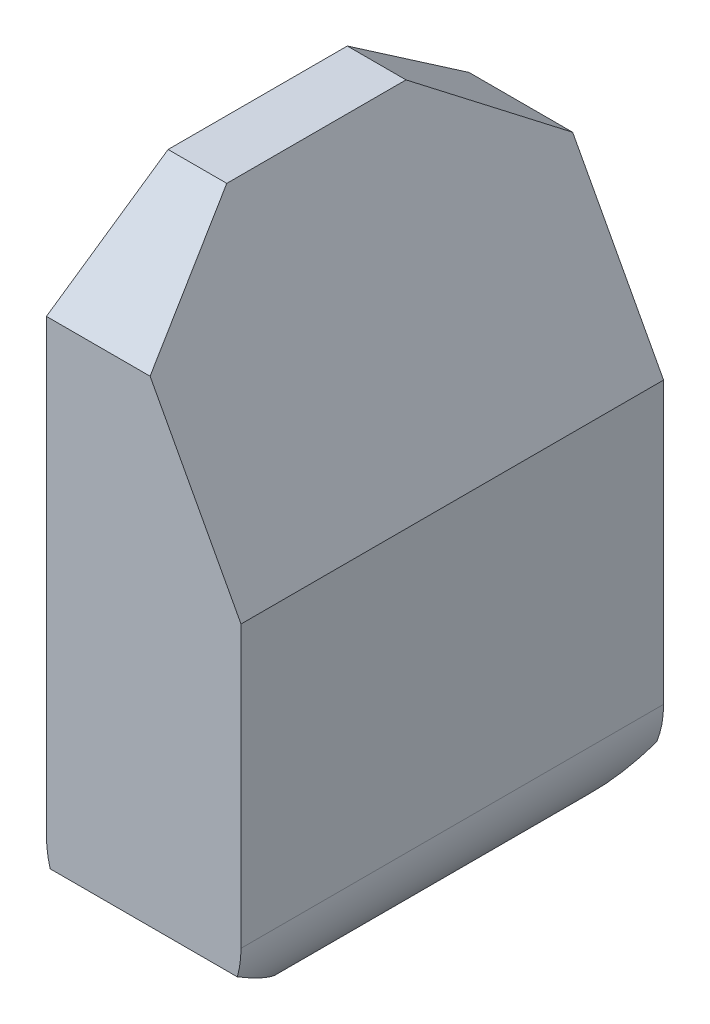
SolidWorks part; units mm, degrees
ref_plane "Front" through (0, 0, 0) normal (0, 0, 1) x (1, 0, 0)
ref_plane "Top" through (0, 0, 0) normal (0, 1, 0) x (1, 0, 0)
ref_plane "Right" through (0, 0, 0) normal (1, 0, 0) x (0, 0, -1)
sketch "Sketch1" plane through (0, 0, 0) normal (0, 0, 1) x (1, 0, 0)
  line L4 (-3.6, 36.195) -> (-3.6, -5.4274)
  line L5 (11.5754, -5.4274) -> (11.5754, 16.4753)
  line L6 (11.5754, 16.4753) -> (0.9764, 36.195)
  line L7 (0.9764, 36.195) -> (-3.6, 36.195)
  line L8 (-3.6, 36.195) -> (-3.6, -5.4274)
  line L9 (11.5754, -5.4274) -> (11.5754, 16.4753)
  line L10 (11.5754, 16.4753) -> (0.9764, 36.195)
  line L11 (0.9764, 36.195) -> (-3.6, 36.195)
  arc A1 (-3.6, -5.4274) -> (11.5754, -5.4274) centre (3.9877, -5.4274) ccw
  arc A2 (-3.6, -5.4274) -> (11.5754, -5.4274) centre (3.9877, -5.4274) ccw
  dimension "D1" = 0
extrude "Boss-Extrude1" add sketch "Sketch1" along normal blind 30.956 and the other way blind 2
sketch "Sketch2" plane through (0, 0, 0) normal (-1, 0, 0) x (0, 0, 1)
  line L0 (-2, 29.668) -> (7.4891, 36.195)
  line L1 (-2, 36.195) -> (-2, -5.4274) construction
  line L2 (-2, 36.195) -> (30.956, 36.195) construction
  line L3 (7.4891, 36.195) -> (21.4669, 36.195)
  line L4 (21.4669, 36.195) -> (30.956, 29.668)
  line L5 (30.956, 36.195) -> (30.956, -5.4274) construction
  line L6 (-2, 29.668) -> (-2, 40.5739)
  line L7 (-2, 40.5739) -> (30.956, 40.5739)
  line L8 (30.956, 40.5739) -> (30.956, 29.668)
  line L9 (-6.3024, -4.8107) -> (9.2596, -17.018)
  line L10 (9.2596, -17.018) -> (16.7145, -17.018)
  line L11 (16.7145, -17.018) -> (37.4948, -3.1334)
  line L12 (37.4948, -3.1334) -> (37.4948, -21.3969)
  line L13 (37.4948, -21.3969) -> (-6.3024, -21.3969)
  line L14 (-6.3024, -21.3969) -> (-6.3024, -4.8107)
extrude "Cut-Extrude1" cut sketch "Sketch2" against normal through all both and the other way through all
